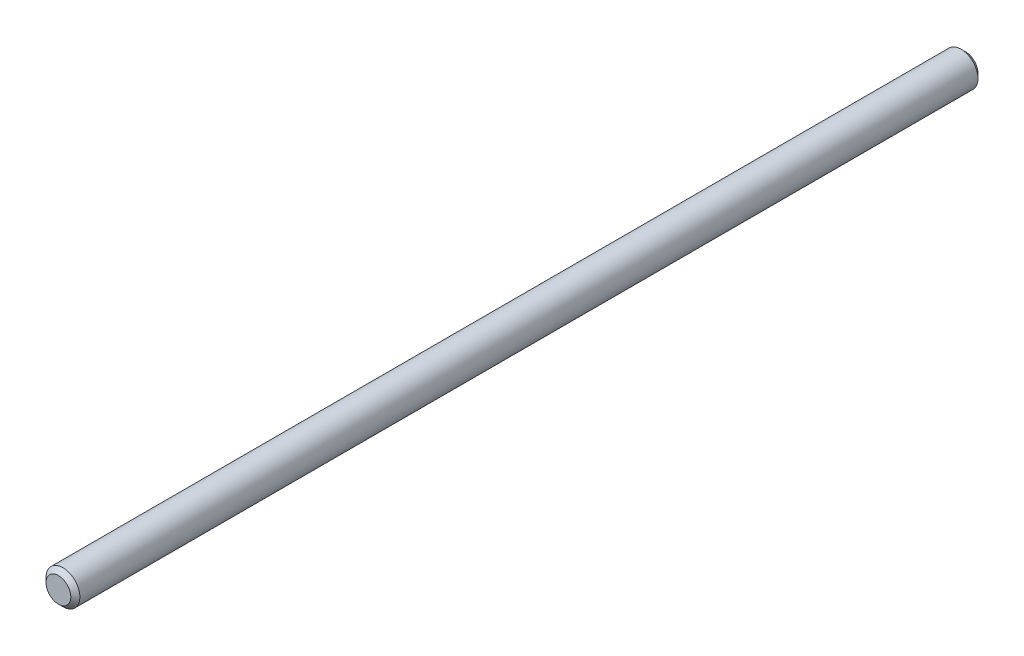
SolidWorks part; units mm, degrees
material "Alloy Steel"
ref_plane "Front Plane" through (0, 0, 0) normal (0, 0, 1) x (1, 0, 0)
ref_plane "Top Plane" through (0, 0, 0) normal (0, 1, 0) x (1, 0, 0)
ref_plane "Right Plane" through (0, 0, 0) normal (1, 0, 0) x (0, 0, -1)
sketch "Sketch1" plane through (0, 0, 0) normal (0, 0, 1) x (1, 0, 0)
  circle A0 centre (0, 0) radius 1.4224
  dimension "D1" = 2.8448
extrude "Extrude1" add sketch "Sketch1" against normal blind 76.2
cosmetic thread "Cosmetic Thread1"
chamfer "Chamfer1" distance 0.381 angle 45 2 edges at (1.4224, 0, -76.2) (1.4224, 0, 0)
